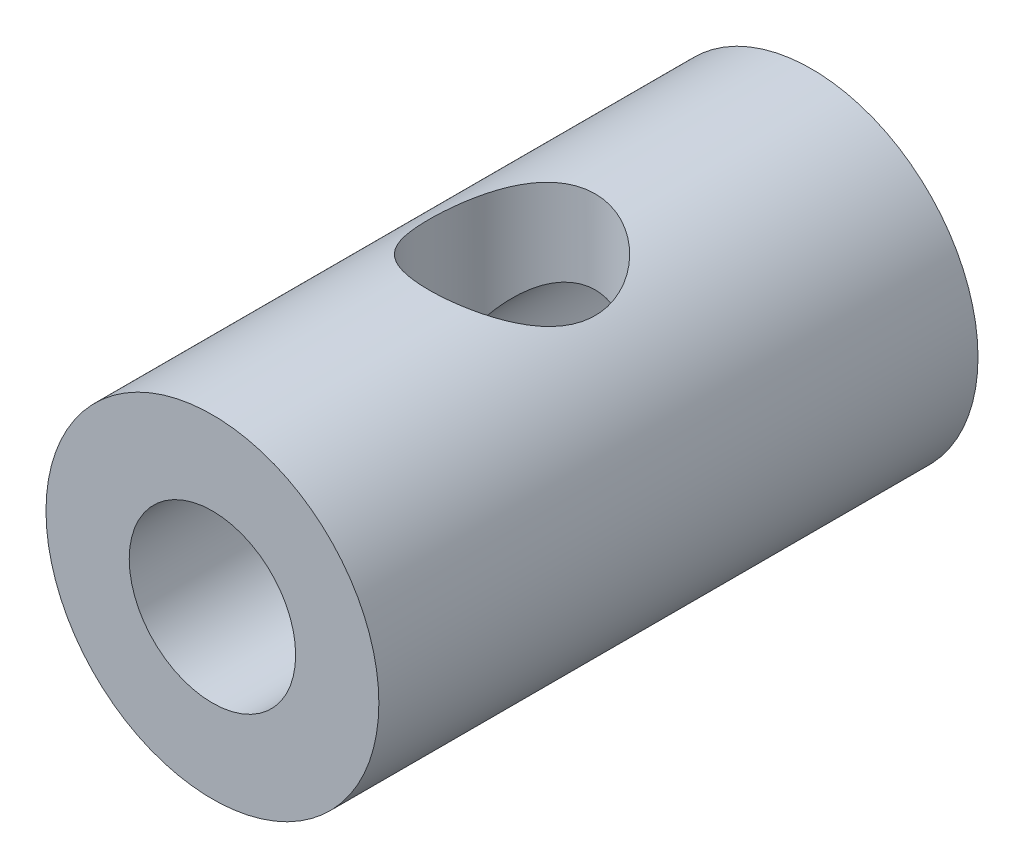
SolidWorks part; units mm, degrees
ref_plane "Front Plane" through (0, 0, 0) normal (0, 0, 1) x (1, 0, 0)
ref_plane "Top Plane" through (0, 0, 0) normal (0, 1, 0) x (1, 0, 0)
ref_plane "Right Plane" through (0, 0, 0) normal (1, 0, 0) x (0, 0, -1)
sketch "Sketch1" plane through (0, 0, 0) normal (0, 0, 1) x (1, 0, 0)
  circle A0 centre (0, 0) radius 50
  circle A1 centre (0, 0) radius 25
  dimension "D1" = 100
  dimension "D2" = 50
extrude "Boss-Extrude1" add sketch "Sketch1" along normal mid plane 180
sketch "Sketch2" plane through (0, 0, 0) normal (0, 1, 0) x (1, 0, 0)
  circle A0 centre (0, 0) radius 25
  dimension "D1" = 50
extrude "Cut-Extrude1" cut sketch "Sketch2" against normal through all both and the other way through all
